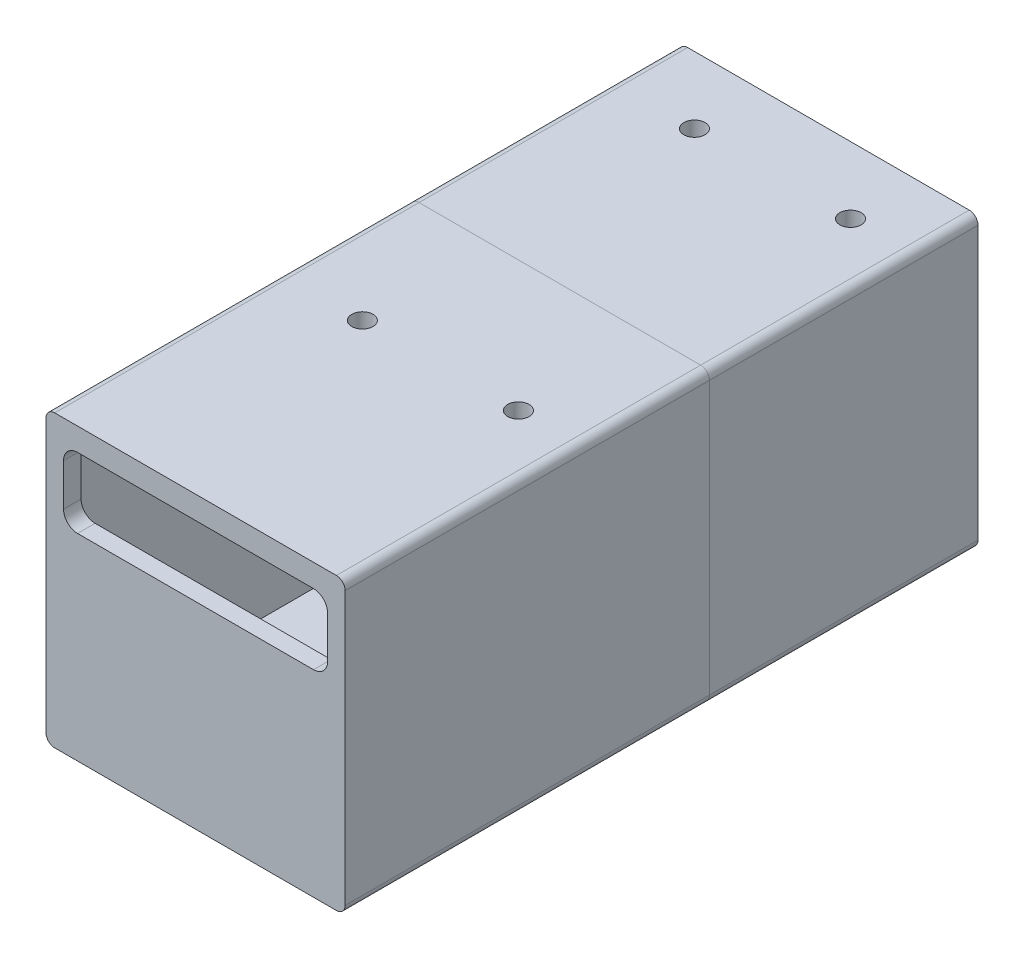
SolidWorks part; units mm, degrees
material "ABS"
ref_plane "X-Y Datum" through (0, 0, 0) normal (0, 0, 1) x (1, 0, 0)
ref_plane "X-Z Datum" through (0, 0, 0) normal (0, 1, 0) x (1, 0, 0)
ref_plane "Y-Z Datum" through (0, 0, 0) normal (1, 0, 0) x (0, 0, -1)
sketch "Sketch1" plane through (0, 0, 0) normal (0, 0, 1) x (1, 0, 0)
  line L0 (-42.608, 40.576) -> (42.608, 40.576)
  line L1 (-38.608, 36.576) -> (38.608, 36.576) construction
  line L2 (-38.608, 36.576) -> (-38.608, -36.576) construction
  line L3 (-38.608, -36.576) -> (38.608, -36.576) construction
  line L4 (38.608, 36.576) -> (38.608, -36.576) construction
  line L5 (-38.608, 36.576) -> (38.608, -36.576) construction
  line L6 (-38.608, -36.576) -> (38.608, 36.576) construction
  line L11 (42.608, 40.576) -> (42.608, -40.576)
  line L12 (-42.608, -40.576) -> (42.608, -40.576)
  line L13 (-42.608, 40.576) -> (-42.608, -40.576)
  point P0 (0, 0)
  point P6 (0, 0)
  dimension "D1" = 77.216
  dimension "D2" = 4
  dimension "D3" = 73.152
extrude "Boss-Extrude1" add sketch "Sketch1" along normal blind 182.776
ref_plane "Plane1" through (0, 0, 80) normal (0, 0, -1) x (-1, 0, 0)
split "Split1" trim tools "Plane1" bodies to split 101 resulting bodies 102 103
shell "Shell2" thickness 4
shell "Shell3" thickness 4
sketch "Sketch4" plane through (0, 0, 80) normal (0, 0, 1) x (1, 0, 0)
  line L14 (40.608, -38.576) -> (40.608, 38.576)
  line L15 (-40.608, -38.576) -> (40.608, -38.576)
  line L16 (-40.608, 38.576) -> (-40.608, -38.576)
  line L17 (40.608, 38.576) -> (-40.608, 38.576)
  line L18 (40.608, -38.576) -> (40.608, 38.576)
  line L19 (-40.608, -38.576) -> (40.608, -38.576)
  line L20 (-40.608, 38.576) -> (-40.608, -38.576)
  line L21 (40.608, 38.576) -> (-40.608, 38.576)
  line L22 (-38.608, 36.576) -> (-38.608, -36.576)
  line L23 (-38.608, -36.576) -> (38.608, -36.576)
  line L24 (38.608, -36.576) -> (38.608, 36.576)
  line L25 (38.608, 36.576) -> (-38.608, 36.576)
  line L26 (-38.608, 36.576) -> (-38.608, -36.576)
  line L27 (-38.608, -36.576) -> (38.608, -36.576)
  line L28 (38.608, -36.576) -> (38.608, 36.576)
  line L29 (38.608, 36.576) -> (-38.608, 36.576)
  dimension "D1" = 2
  dimension "D2" = 0
extrude "Boss-Extrude2" add sketch "Sketch4" along normal blind 30
sketch "Sketch5" plane through (0, 0, 80) normal (0, 0, -1) x (-1, 0, 0)
  line L0 (40.989, 38.957) -> (-40.989, 38.957)
  line L1 (-40.989, 38.957) -> (-40.989, -38.957)
  line L2 (-40.989, -38.957) -> (40.989, -38.957)
  line L3 (40.989, -38.957) -> (40.989, 38.957)
  line L4 (38.608, -36.576) -> (38.608, 36.576)
  line L5 (-38.608, -36.576) -> (38.608, -36.576)
  line L6 (-38.608, 36.576) -> (-38.608, -36.576)
  line L7 (38.608, 36.576) -> (-38.608, 36.576)
  line L8 (38.608, -36.576) -> (38.608, 36.576)
  line L9 (-38.608, -36.576) -> (38.608, -36.576)
  line L10 (-38.608, 36.576) -> (-38.608, -36.576)
  line L11 (38.608, 36.576) -> (-38.608, 36.576)
  line L12 (-40.608, 38.576) -> (-40.608, -38.576)
  line L13 (-40.608, -38.576) -> (40.608, -38.576)
  line L14 (40.608, -38.576) -> (40.608, 38.576)
  line L15 (40.608, 38.576) -> (-40.608, 38.576)
  line L16 (-40.608, 38.576) -> (-40.608, -38.576) construction
  line L17 (-40.608, -38.576) -> (40.608, -38.576) construction
  line L18 (40.608, -38.576) -> (40.608, 38.576) construction
  line L19 (40.608, 38.576) -> (-40.608, 38.576) construction
  line L24 (-42.608, -40.576) -> (42.608, -40.576)
  line L25 (42.608, -40.576) -> (42.608, 40.576)
  line L26 (42.608, 40.576) -> (-42.608, 40.576)
  line L27 (-42.608, 40.576) -> (-42.608, -40.576)
  line L28 (-42.608, -40.576) -> (42.608, -40.576)
  line L29 (42.608, -40.576) -> (42.608, 40.576)
  line L30 (42.608, 40.576) -> (-42.608, 40.576)
  line L31 (-42.608, 40.576) -> (-42.608, -40.576)
  line M21 (38.608, -36.576) -> (-38.608, -36.576)
  line M22 (-38.608, -36.576) -> (-38.608, 36.576)
  line M23 (-38.608, 36.576) -> (38.608, 36.576)
  line M24 (38.608, 36.576) -> (38.608, -36.576)
  dimension "D1" = 0
  dimension "D2" = 0
  dimension "D3" = 0.381
  dimension "D4" = 0
extrude "Cut-Extrude2" cut sketch "Sketch5" against normal blind 31 contours L2 L3 L0 L1 M24 M21 M22 M23
sketch "Sketch6" plane through (0, 0, 182.776) normal (0, 0, 1) x (1, 0, 0)
  line L0 (0, -40.576) -> (0, 40.576) construction
  line L1 (-42.608, -40.576) -> (42.608, -40.576) construction
  line L2 (42.608, 40.576) -> (-42.608, 40.576) construction
  line L4 (-37.608, 35.576) -> (37.608, 35.576)
  line L5 (-37.608, 35.576) -> (-37.608, 15.576)
  line L6 (-37.608, 15.576) -> (37.608, 15.576)
  line L7 (37.608, 35.576) -> (37.608, 15.576)
  line L8 (-37.608, 35.576) -> (37.608, 15.576) construction
  line L9 (-37.608, 15.576) -> (37.608, 35.576) construction
  line L10 (38.608, 36.576) -> (-38.608, 36.576) construction
  line L11 (38.608, -36.576) -> (38.608, 36.576) construction
  point P6 (0, 25.576)
  dimension "D1" = 20
  dimension "D2" = 1
  dimension "D3" = 1
extrude "Cut-Extrude3" cut sketch "Sketch6" against normal blind 4
fillet "Fillet3" radius 4 4 edges at (37.608, 35.576, 180.776) (37.608, 15.576, 180.776) (-37.608, 35.576, 180.776) (-37.608, 15.576, 180.776)
sketch "Sketch7" plane through (0, 0, 182.776) normal (0, 0, 1) x (1, 0, 0)
  line L0 (-37.608, 31.576) -> (-37.608, 19.576) construction
  line L1 (-33.608, 15.576) -> (33.608, 15.576) construction
  line L2 (33.608, 35.576) -> (-33.608, 35.576) construction
  line L3 (37.608, 19.576) -> (37.608, 31.576) construction
  line L4 (-42.608, 40.576) -> (-42.608, -40.576)
  line L5 (-42.608, -40.576) -> (42.608, -40.576)
  line L6 (42.608, -40.576) -> (42.608, 40.576)
  line L7 (42.608, 40.576) -> (-42.608, 40.576)
  line L8 (-42.608, 40.576) -> (-42.608, -40.576)
  line L9 (-42.608, -40.576) -> (42.608, -40.576)
  line L10 (42.608, -40.576) -> (42.608, 40.576)
  line L11 (42.608, 40.576) -> (-42.608, 40.576)
  line L12 (-33.608, 15.576) -> (33.608, 15.576)
  line L13 (-37.608, 31.576) -> (-37.608, 19.576)
  line L14 (33.608, 35.576) -> (-33.608, 35.576)
  line L15 (37.608, 19.576) -> (37.608, 31.576)
  arc A0 (-37.608, 19.576) -> (-33.608, 15.576) centre (-33.608, 19.576) ccw construction
  arc A1 (-33.608, 35.576) -> (-37.608, 31.576) centre (-33.608, 31.576) ccw construction
  arc A2 (37.608, 31.576) -> (33.608, 35.576) centre (33.608, 31.576) ccw construction
  arc A3 (33.608, 15.576) -> (37.608, 19.576) centre (33.608, 19.576) ccw construction
  arc A12 (-37.608, 19.576) -> (-33.608, 15.576) centre (-33.608, 19.576) ccw
  arc A13 (-33.608, 35.576) -> (-37.608, 31.576) centre (-33.608, 31.576) ccw
  arc A14 (37.608, 31.576) -> (33.608, 35.576) centre (33.608, 31.576) ccw
  arc A15 (33.608, 15.576) -> (37.608, 19.576) centre (33.608, 19.576) ccw
  dimension "D1" = 0
extrude "Boss-Extrude3" add sketch "Sketch7" along normal blind 4
sketch "Sketch8" plane through (0, 0, 0) normal (0, 0, -1) x (-1, 0, 0)
  line L4 (42.608, 40.576) -> (-42.608, 40.576)
  line L5 (-42.608, 40.576) -> (-42.608, -40.576)
  line L6 (-42.608, -40.576) -> (42.608, -40.576)
  line L7 (42.608, -40.576) -> (42.608, 40.576)
  line L8 (42.608, 40.576) -> (-42.608, 40.576)
  line L9 (-42.608, 40.576) -> (-42.608, -40.576)
  line L10 (-42.608, -40.576) -> (42.608, -40.576)
  line L11 (42.608, -40.576) -> (42.608, 40.576)
  dimension "D1" = 0
extrude "Boss-Extrude4" add sketch "Sketch8" along normal blind 4
sketch "Sketch10" plane through (0, 0, 4) normal (0, 0, 1) x (1, 0, 0)
  line L4 (-38.608, 36.576) -> (-38.608, -36.576)
  line L5 (-38.608, -36.576) -> (38.608, -36.576)
  line L6 (38.608, -36.576) -> (38.608, 36.576)
  line L7 (38.608, 36.576) -> (-38.608, 36.576)
  line L8 (-38.608, 36.576) -> (-38.608, -36.576)
  line L9 (-38.608, -36.576) -> (38.608, -36.576)
  line L10 (38.608, -36.576) -> (38.608, 36.576)
  line L11 (38.608, 36.576) -> (-38.608, 36.576)
  dimension "D1" = 0
extrude "Boss-Extrude5" add sketch "Sketch10" along normal blind 4.5
sketch "Sketch12" plane through (0, 0, 186.776) normal (0, 0, 1) x (1, 0, 0)
  line L0 (-30.9726, -0.1002) -> (4.6151, -9.5785)
  line L1 (-4.2066, 6.35) -> (31.9531, 6.35)
  line L2 (-35.7631, -3.7819) -> (-35.7631, -8.89)
  line L3 (-31.9531, -12.7) -> (4.2066, -12.7)
  line L4 (35.7631, 2.54) -> (35.7631, -2.5681)
  line L5 (-35.7631, 6.35) -> (35.7631, -12.7) construction
  line L6 (-35.7631, -12.7) -> (35.7631, 6.35) construction
  line L7 (-4.6151, 3.2285) -> (30.9726, -6.2498)
  line L8 (-34.4763, 11.1816) -> (37.0499, -7.8684) construction
  line L9 (-37.0499, 1.5184) -> (34.4763, -17.5316) construction
  arc A0 (35.7631, -2.5681) -> (30.9726, -6.2498) centre (31.9531, -2.5681) cw
  arc A1 (35.7631, 2.54) -> (31.9531, 6.35) centre (31.9531, 2.54) ccw
  arc A2 (-35.7631, -3.7819) -> (-30.9726, -0.1002) centre (-31.9531, -3.7819) cw
  arc A3 (-31.9531, -12.7) -> (-35.7631, -8.89) centre (-31.9531, -8.89) cw
  arc A4 (4.2066, -12.7) -> (4.6151, -9.5785) centre (4.2066, -11.1125) ccw
  arc A5 (-4.2066, 6.35) -> (-4.6151, 3.2285) centre (-4.2066, 4.7625) ccw
  point P0 (0, -3.175)
  dimension "D2" = 3.81
  dimension "D5" = 1.5875
  dimension "D1" = 3.175
  dimension "D3" = 5
  dimension "D4" = 5
extrude "Cut-Extrude6" [suppressed] cut sketch "Sketch12" against normal up to surface (8 mm away)
sketch "Sketch24" plane through (0, 0, -4) normal (0, 0, -1) x (-1, 0, 0)
  line L4 (-42.608, 40.576) -> (-42.608, -40.576)
  line L5 (-42.608, -40.576) -> (42.608, -40.576)
  line L6 (42.608, -40.576) -> (42.608, 40.576)
  line L7 (42.608, 40.576) -> (-42.608, 40.576)
  line L8 (-42.608, 40.576) -> (-42.608, -40.576)
  line L9 (-42.608, -40.576) -> (42.608, -40.576)
  line L10 (42.608, -40.576) -> (42.608, 40.576)
  line L11 (42.608, 40.576) -> (-42.608, 40.576)
  dimension "D1" = 0
extrude "Cut-Extrude7" cut sketch "Sketch24" against normal blind 7.5
sketch "Sketch25" plane through (0, 0, 186.776) normal (0, 0, 1) x (1, 0, 0)
  line L4 (-42.608, -40.576) -> (42.608, -40.576)
  line L5 (42.608, -40.576) -> (42.608, 40.576)
  line L6 (42.608, 40.576) -> (-42.608, 40.576)
  line L7 (-42.608, 40.576) -> (-42.608, -40.576)
  line L8 (-42.608, -40.576) -> (42.608, -40.576)
  line L9 (42.608, -40.576) -> (42.608, 40.576)
  line L10 (42.608, 40.576) -> (-42.608, 40.576)
  line L11 (-42.608, 40.576) -> (-42.608, -40.576)
  dimension "D1" = 0
extrude "Cut-Extrude8" cut sketch "Sketch25" against normal blind 3
sketch "Sketch27" plane through (0, 40.576, 0) normal (0, 1, 0) x (1, 0, 0)
  line L4 (-42.608, -183.776) -> (42.608, -183.776)
  line L5 (42.608, -183.776) -> (42.608, -80)
  line L6 (42.608, -80) -> (-42.608, -80)
  line L7 (-42.608, -80) -> (-42.608, -183.776)
  line L8 (-42.608, -183.776) -> (42.608, -183.776)
  line L9 (42.608, -183.776) -> (42.608, -80)
  line L10 (42.608, -80) -> (-42.608, -80)
  line L11 (-42.608, -80) -> (-42.608, -183.776)
  dimension "D1" = 0
extrude "Boss-Extrude15" add sketch "Sketch27" along normal blind 1.5
sketch "Sketch28" plane through (0, 40.576, 0) normal (0, 1, 0) x (1, 0, 0)
  line L4 (42.608, -3.5) -> (-42.608, -3.5)
  line L5 (-42.608, -3.5) -> (-42.608, -80)
  line L6 (-42.608, -80) -> (42.608, -80)
  line L7 (42.608, -80) -> (42.608, -3.5)
  line L8 (42.608, -3.5) -> (-42.608, -3.5)
  line L9 (-42.608, -3.5) -> (-42.608, -80)
  line L10 (-42.608, -80) -> (42.608, -80)
  line L11 (42.608, -80) -> (42.608, -3.5)
  dimension "D1" = 0
extrude "Boss-Extrude16" add sketch "Sketch28" along normal blind 1.5
fillet "Fillet4" radius 2.5 4 edges at (42.608, -40.576, 131.888) (-42.608, -40.576, 131.888) (-42.608, 42.076, 131.888) (42.608, 42.076, 131.888)
fillet "Fillet5" radius 2.5 4 edges at (42.608, 42.076, 41.75) (-42.608, 42.076, 41.75) (-42.608, -40.576, 41.75) (42.608, -40.576, 41.75)
sketch "Sketch29" plane through (0, 42.076, 0) normal (0, 1, 0) x (1, 0, 0)
  circle A0 centre (25.3395, -117.148) radius 3.025
  circle A1 centre (-19.1105, -117.148) radius 3.025
  circle A2 centre (-19.1105, -22.55) radius 3.025
  circle A3 centre (25.3395, -22.55) radius 3.025
  point P0 (-19.1105, -22.55)
  point P1 (25.3395, -22.55)
  point P3 (-19.1105, -117.148)
  point P5 (25.3395, -117.148)
  dimension "D1" = 6.05
extrude "Cut-Extrude9" cut sketch "Sketch29" against normal blind 5
other "Save Bodies1"
